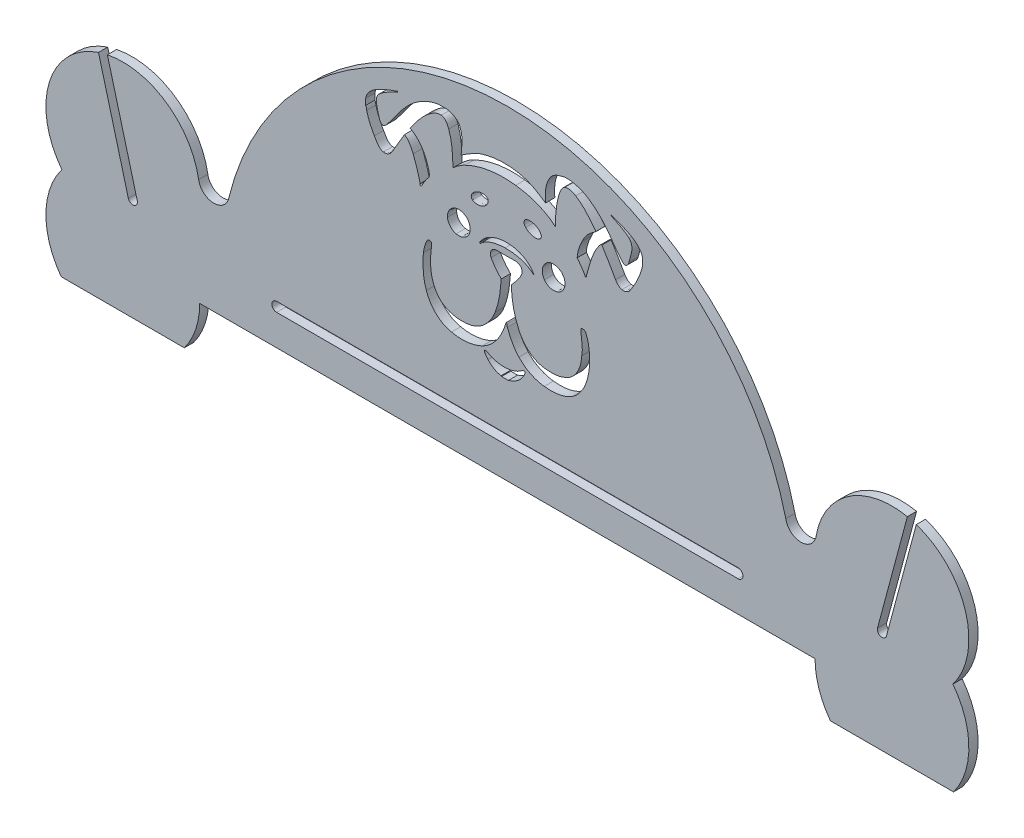
SolidWorks part; units mm, degrees
ref_plane "Plano frontal" through (0, 0, 0) normal (0, 0, 1) x (1, 0, 0)
ref_plane "Plano superior" through (0, 0, 0) normal (0, 1, 0) x (1, 0, 0)
ref_plane "Plano direito" through (0, 0, 0) normal (1, 0, 0) x (0, 0, -1)
sketch "Esboço1" plane through (0, 0, 0) normal (0, 0, 1) x (1, 0, 0)
  line L0 (-200, 0) -> (200, 0)
  line L1 (150, 26.2) -> (144.1525, 26.2)
  line L2 (0, 0) -> (0, 26.2) construction
  line L3 (150, 26.2) -> (-150, 26.2) construction
  line L4 (150, 20) -> (150, 26.2) construction
  line L5 (-144.1525, 26.2) -> (144.1525, 26.2)
  line L6 (150, 20) -> (-150, 20)
  line L13 (140, 61) -> (200, 61)
  line L14 (289.6201, 30.5) -> (200, 30.5) construction
  line L15 (200, 30.5) -> (200, 61) construction
  line L16 (250, 61) -> (262.9328, 109.2659) construction
  line L17 (210, -30) -> (290, -30)
  line L18 (260.0199, 109.9857) -> (240.6084, 37.5413)
  line L19 (246.404, 35.9884) -> (265.8154, 108.4328)
  line L20 (240.6084, 37.5413) -> (246.404, 35.9884) construction
  line L21 (243.5062, 36.7648) -> (250, 61) construction
  line L22 (-243.5062, 36.7648) -> (-250, 61) construction
  line L23 (-240.6084, 37.5413) -> (-246.404, 35.9884) construction
  line L24 (-250, 61) -> (-262.9328, 109.2659) construction
  line L25 (-200, 30.5) -> (-200, 61) construction
  line L26 (-289.6201, 30.5) -> (-200, 30.5) construction
  line L27 (-150, 20) -> (-150, 26.2) construction
  line L28 (-246.404, 35.9884) -> (-265.8154, 108.4328)
  line L29 (-260.0199, 109.9857) -> (-240.6084, 37.5413)
  line L30 (-210, -30) -> (-290, -30)
  line L31 (140, 61) -> (-200, 61)
  line L39 (-150, 26.2) -> (-144.1525, 26.2)
  arc A0 (150, 20) -> (150, 26.2) centre (150, 23.1) ccw
  arc A1 (200, 61) -> (260.0199, 109.9857) centre (250, 61) cw
  arc A2 (200, 0) -> (210, -30) centre (250, 0) ccw
  arc A3 (290, -30) -> (289.6201, 30.5) centre (250, 0) ccw
  arc A4 (240.6084, 37.5413) -> (246.404, 35.9884) centre (243.5062, 36.7648) ccw
  arc A5 (265.8154, 108.4328) -> (289.6201, 30.5) centre (250, 61) cw
  arc A6 (-265.8154, 108.4328) -> (-289.6201, 30.5) centre (-250, 61) ccw
  arc A7 (-240.6084, 37.5413) -> (-246.404, 35.9884) centre (-243.5062, 36.7648) cw
  arc A8 (-290, -30) -> (-289.6201, 30.5) centre (-250, 0) cw
  arc A9 (-200, 0) -> (-210, -30) centre (-250, 0) cw
  arc A10 (-200, 61) -> (-260.0199, 109.9857) centre (-250, 61) ccw
  arc A11 (-150, 20) -> (-150, 26.2) centre (-150, 23.1) cw
  point P45 (0, 20)
  point P54 (0, 20)
  dimension "D7" = 30
  dimension "D9" = 15
  dimension "D10" = 6
  dimension "D11" = 75
  dimension "D1" = 3.1
  dimension "D6" = 50
  dimension "D2" = 200
  dimension "D3" = 20
  dimension "D4" = 150
  dimension "D5" = 61
  dimension "D8" = 140
extrude "Ressalto-extrusão2" add sketch "Esboço1" along normal blind 6
sketch "Esboço7" plane through (0, 0, 6) normal (0, 0, 1) x (1, 0, 0)
  line L0 (0, 0) -> (0, 211) construction
  line L1 (200, 61) -> (-200, 61) construction
  line L2 (-200.6993, 69.3333) -> (-180.9791, 69.3333) construction
  line L3 (0, 211) -> (-172.3956, 211) construction
  line L4 (-200, 61) -> (-204.6025, 61)
  line L5 (-200, 61) -> (200, 61)
  line L6 (200, 61) -> (209.3232, 61)
  line L7 (209.3232, 61) -> (200.6993, 69.3333)
  line L8 (-204.6025, 61) -> (-204.6025, 69.3333)
  line L9 (-204.6025, 69.3333) -> (-200.6993, 69.3333)
  arc A0 (-200.6993, 69.3333) -> (-180.9791, 69.3333) centre (-190.8392, 71) ccw
  arc A1 (-200, 61) -> (-260.0199, 109.9857) centre (-250, 61) ccw construction
  arc A2 (-180.9791, 69.3333) -> (180.9791, 69.3333) centre (0, 24.5663) cw
  arc A3 (200.6993, 69.3333) -> (180.9791, 69.3333) centre (190.8392, 71) cw
  arc A4 (260.0199, 109.9857) -> (200, 61) centre (250, 61) ccw construction
  arc M8 (260.0199, 109.9857) -> (200, 61) centre (250, 61) ccw
  line M9 (200, 61) -> (-200, 61)
  arc M10 (-200, 61) -> (-260.0199, 109.9857) centre (-250, 61) ccw
  dimension "D2" = 10
  dimension "D1" = 211
extrude "Ressalto-extrusão4" add sketch "Esboço7" against normal up to vertex (6 mm away) contours L5 A3 A2 A0 | A3 M8 M9 | L6 L7 M8 | A0 L5 M10 | L9 L8 L4 M10
sketch "Esboço8" plane through (0, 0, 6) normal (0, 0, 1) x (1, 0, 0)
  line L0 (-44.7783, 189.7384) -> (-39.1773, 189.7384)
  line L1 (37.1274, 189.7384) -> (41.16, 189.7384)
  line L2 (87.8647, 169.7987) -> (87.8647, 165.1092)
  line L3 (-92.1581, 165.343) -> (-92.1581, 169.3644)
  line L4 (0.6392, 56.9718) -> (-3.8029, 56.9718)
  spline S0 degree 3 poles (-39.1773, 189.7384) (-36.0719, 189.0183) (-32.5885, 187.7289) (-31.1078, 184.635) knots 0.016129 0.016129 0.016129 0.016129 0.032258 0.032258 0.032258 0.032258
  spline S1 degree 3 poles (-31.1078, 184.635) (-28.6572, 179.6684) (-29.5867, 173.8604) (-30.0502, 168.5429) knots 0.032258 0.032258 0.032258 0.032258 0.048387 0.048387 0.048387 0.048387
  spline S2 degree 3 poles (-30.0502, 168.5429) (-25.9705, 171.0701) (-21.9875, 173.937) (-17.4035, 175.5257) knots 0.048387 0.048387 0.048387 0.048387 0.064516 0.064516 0.064516 0.064516
  spline S3 degree 3 poles (-17.4035, 175.5257) (-7.8804, 178.6176) (2.7207, 178.9302) (12.2934, 175.8452) knots 0.064516 0.064516 0.064516 0.064516 0.080645 0.080645 0.080645 0.080645
  spline S4 degree 3 poles (12.2934, 175.8452) (16.8276, 174.2565) (20.8602, 171.5855) (24.8432, 168.9706) knots 0.080645 0.080645 0.080645 0.080645 0.096774 0.096774 0.096774 0.096774
  spline S5 degree 3 poles (24.8432, 168.9706) (24.4225, 174.6706) (24.6092, 181.0503) (28.5111, 185.634) knots 0.096774 0.096774 0.096774 0.096774 0.112903 0.112903 0.112903 0.112903
  spline S6 degree 3 poles (28.5111, 185.634) (30.6353, 188.2645) (34.0312, 189.0002) (37.1274, 189.7384) knots 0.112903 0.112903 0.112903 0.112903 0.129032 0.129032 0.129032 0.129032
  spline S7 degree 3 poles (41.16, 189.7384) (43.8266, 189.0274) (46.7114, 188.6628) (49.2047, 187.3059) knots 0.145161 0.145161 0.145161 0.145161 0.16129 0.16129 0.16129 0.16129
  spline S8 degree 3 poles (49.2047, 187.3059) (55.9174, 184.0833) (61.3586, 178.7279) (65.742, 172.796) knots 0.16129 0.16129 0.16129 0.16129 0.177419 0.177419 0.177419 0.177419
  spline S9 degree 3 poles (65.742, 172.796) (68.8317, 168.6983) (71.4938, 164.2135) (75.1032, 160.5456) knots 0.177419 0.177419 0.177419 0.177419 0.193548 0.193548 0.193548 0.193548
  spline S10 degree 3 poles (75.1032, 160.5456) (76.8765, 158.5967) (78.7081, 161.0585) (79.039, 162.8047) knots 0.193548 0.193548 0.193548 0.193548 0.209677 0.209677 0.209677 0.209677
  spline S11 degree 3 poles (79.039, 162.8047) (80.0583, 167.0398) (82.6957, 172.562) (79.1313, 176.2749) knots 0.209677 0.209677 0.209677 0.209677 0.225806 0.225806 0.225806 0.225806
  spline S12 degree 3 poles (79.1313, 176.2749) (76.2463, 178.9372) (72.6324, 180.5842) (69.1196, 182.2427) knots 0.225806 0.225806 0.225806 0.225806 0.241935 0.241935 0.241935 0.241935
  spline S13 degree 3 poles (69.1196, 182.2427) (68.521, 182.5983) (67.567, 182.7177) (67.3555, 183.4578) knots 0.241935 0.241935 0.241935 0.241935 0.258065 0.258065 0.258065 0.258065
  spline S14 degree 3 poles (67.3555, 183.4578) (70.8704, 182.6117) (74.2684, 181.1738) (77.5561, 179.6528) knots 0.258065 0.258065 0.258065 0.258065 0.274194 0.274194 0.274194 0.274194
  spline S15 degree 3 poles (77.5561, 179.6528) (81.8832, 177.5598) (86.5324, 174.7224) (87.8647, 169.7987) knots 0.274194 0.274194 0.274194 0.274194 0.290323 0.290323 0.290323 0.290323
  spline S16 degree 3 poles (87.8647, 165.1092) (86.4175, 158.644) (83.4383, 152.5345) (79.6892, 147.0665) knots 0.306452 0.306452 0.306452 0.306452 0.322581 0.322581 0.322581 0.322581
  spline S17 degree 3 poles (79.6892, 147.0665) (78.4066, 145.597) (76.4669, 144.5415) (74.4596, 145.0478) knots 0.322581 0.322581 0.322581 0.322581 0.33871 0.33871 0.33871 0.33871
  spline S18 degree 3 poles (74.4596, 145.0478) (72.6009, 145.4574) (71.1877, 146.9178) (70.2989, 148.5424) knots 0.33871 0.33871 0.33871 0.33871 0.354839 0.354839 0.354839 0.354839
  spline S19 degree 3 poles (70.2989, 148.5424) (67.4612, 153.6169) (64.5921, 158.6823) (61.4305, 163.5654) knots 0.354839 0.354839 0.354839 0.354839 0.370968 0.370968 0.370968 0.370968
  spline S20 degree 3 poles (61.4305, 163.5654) (60.6811, 163.8736) (60.3009, 162.8071) (59.7967, 162.456) knots 0.370968 0.370968 0.370968 0.370968 0.387097 0.387097 0.387097 0.387097
  spline S21 degree 3 poles (59.7967, 162.456) (55.204, 156.5242) (53.5433, 149.0016) (51.5427, 141.9268) knots 0.387097 0.387097 0.387097 0.387097 0.403226 0.403226 0.403226 0.403226
  spline S22 degree 3 poles (51.5427, 141.9268) (51.3402, 141.7513) (51.4618, 139.6584) (50.6921, 140.4055) knots 0.403226 0.403226 0.403226 0.403226 0.419355 0.419355 0.419355 0.419355
  spline S23 degree 3 poles (50.6921, 140.4055) (49.2295, 143.2657) (47.2987, 145.8467) (45.4017, 148.4121) knots 0.419355 0.419355 0.419355 0.419355 0.435484 0.435484 0.435484 0.435484
  spline S24 degree 3 poles (45.4017, 148.4121) (45.4469, 152.2309) (46.9252, 155.8583) (48.5903, 159.2381) knots 0.435484 0.435484 0.435484 0.435484 0.451613 0.451613 0.451613 0.451613
  spline S25 degree 3 poles (48.5903, 159.2381) (50.2039, 162.8339) (52.7737, 166.0295) (56.1445, 168.1154) knots 0.451613 0.451613 0.451613 0.451613 0.467742 0.467742 0.467742 0.467742
  spline S26 degree 3 poles (56.1445, 168.1154) (56.6105, 168.453) (57.2135, 168.7208) (57.5127, 169.2519) knots 0.467742 0.467742 0.467742 0.467742 0.483871 0.483871 0.483871 0.483871
  spline S27 degree 3 poles (57.5127, 169.2519) (53.7818, 174.2722) (49.801, 179.4007) (44.4432, 182.7762) knots 0.483871 0.483871 0.483871 0.483871 0.5 0.5 0.5 0.5
  spline S28 degree 3 poles (44.4432, 182.7762) (41.9363, 184.2634) (38.1514, 185.5732) (35.9326, 182.9425) knots 0.5 0.5 0.5 0.5 0.516129 0.516129 0.516129 0.516129
  spline S29 degree 3 poles (35.9326, 182.9425) (33.626, 179.9476) (32.987, 176.1309) (32.2263, 172.5238) knots 0.516129 0.516129 0.516129 0.516129 0.532258 0.532258 0.532258 0.532258
  spline S30 degree 3 poles (32.2263, 172.5238) (31.6682, 167.9916) (31.0832, 163.4485) (31.1304, 158.8669) knots 0.532258 0.532258 0.532258 0.532258 0.548387 0.548387 0.548387 0.548387
  spline S31 degree 3 poles (31.1304, 158.8669) (23.9992, 165.0304) (14.7191, 168.0727) (5.4819, 169.2383) knots 0.548387 0.548387 0.548387 0.548387 0.564516 0.564516 0.564516 0.564516
  spline S32 degree 3 poles (5.4819, 169.2383) (-5.6999, 170.5659) (-17.4081, 169.1326) (-27.5524, 164.0537) knots 0.564516 0.564516 0.564516 0.564516 0.580645 0.580645 0.580645 0.580645
  spline S33 degree 3 poles (-27.5524, 164.0537) (-30.4733, 162.7014) (-33.0521, 160.7661) (-35.4149, 158.6079) knots 0.580645 0.580645 0.580645 0.580645 0.596774 0.596774 0.596774 0.596774
  spline S34 degree 3 poles (-35.4149, 158.6079) (-35.5071, 165.514) (-35.8267, 172.5847) (-38.1556, 179.1599) knots 0.596774 0.596774 0.596774 0.596774 0.612903 0.612903 0.612903 0.612903
  spline S35 degree 3 poles (-38.1556, 179.1599) (-39.0356, 181.3967) (-40.3071, 184.1081) (-42.96, 184.4773) knots 0.612903 0.612903 0.612903 0.612903 0.629032 0.629032 0.629032 0.629032
  spline S36 degree 3 poles (-42.96, 184.4773) (-45.8202, 184.7067) (-48.3405, 183.0304) (-50.5817, 181.4711) knots 0.629032 0.629032 0.629032 0.629032 0.645161 0.645161 0.645161 0.645161
  spline S37 degree 3 poles (-50.5817, 181.4711) (-55.6877, 177.5148) (-59.6886, 172.3349) (-63.3206, 167.0443) knots 0.645161 0.645161 0.645161 0.645161 0.66129 0.66129 0.66129 0.66129
  spline S38 degree 3 poles (-63.3206, 167.0443) (-56.2771, 163.6756) (-52.7083, 156.1148) (-50.8856, 148.9026) knots 0.66129 0.66129 0.66129 0.66129 0.677419 0.677419 0.677419 0.677419
  spline S39 degree 3 poles (-50.8856, 148.9026) (-50.8067, 147.6244) (-50.2847, 145.9211) (-51.4616, 144.9894) knots 0.677419 0.677419 0.677419 0.677419 0.693548 0.693548 0.693548 0.693548
  spline S40 degree 3 poles (-51.4616, 144.9894) (-53.1719, 142.946) (-54.5467, 140.644) (-55.7957, 138.2969) knots 0.693548 0.693548 0.693548 0.693548 0.709677 0.709677 0.709677 0.709677
  spline S41 degree 3 poles (-55.7957, 138.2969) (-56.0027, 137.6197) (-57.5712, 138.0111) (-56.6598, 139.0913) knots 0.709677 0.709677 0.709677 0.709677 0.725806 0.725806 0.725806 0.725806
  spline S42 degree 3 poles (-56.6598, 139.0913) (-57.938, 144.0038) (-59.2454, 148.9476) (-61.2414, 153.6258) knots 0.725806 0.725806 0.725806 0.725806 0.741935 0.741935 0.741935 0.741935
  spline S43 degree 3 poles (-61.2414, 153.6258) (-62.65, 156.5176) (-63.9754, 159.9875) (-66.8963, 161.5987) knots 0.741935 0.741935 0.741935 0.741935 0.758065 0.758065 0.758065 0.758065
  spline S44 degree 3 poles (-66.8963, 161.5987) (-69.349, 157.8835) (-71.4644, 153.9611) (-73.6674, 150.0952) knots 0.758065 0.758065 0.758065 0.758065 0.774194 0.774194 0.774194 0.774194
  spline S45 degree 3 poles (-73.6674, 150.0952) (-74.8961, 147.3948) (-77.2274, 144.2781) (-80.6455, 144.9917) knots 0.774194 0.774194 0.774194 0.774194 0.790323 0.790323 0.790323 0.790323
  spline S46 degree 3 poles (-80.6455, 144.9917) (-83.7171, 145.5722) (-84.9706, 148.7383) (-86.4671, 151.0853) knots 0.790323 0.790323 0.790323 0.790323 0.806452 0.806452 0.806452 0.806452
  spline S47 degree 3 poles (-86.4671, 151.0853) (-88.571, 154.8321) (-90.5198, 158.7475) (-91.4648, 162.9624) knots 0.806452 0.806452 0.806452 0.806452 0.822581 0.822581 0.822581 0.822581
  spline S48 degree 3 poles (-91.4648, 162.9624) (-91.6765, 163.7611) (-91.5278, 164.713) (-92.1581, 165.343) knots 0.822581 0.822581 0.822581 0.822581 0.83871 0.83871 0.83871 0.83871
  spline S49 degree 3 poles (-92.1581, 169.3644) (-91.1228, 174.8214) (-85.8324, 177.7714) (-81.1811, 179.9115) knots 0.854839 0.854839 0.854839 0.854839 0.870968 0.870968 0.870968 0.870968
  spline S50 degree 3 poles (-81.1811, 179.9115) (-78.3773, 181.2886) (-75.4203, 182.3103) (-72.4703, 183.3073) knots 0.870968 0.870968 0.870968 0.870968 0.887097 0.887097 0.887097 0.887097
  spline S51 degree 3 poles (-72.4703, 183.3073) (-71.0031, 184.4346) (-71.2753, 183.0145) (-71.8853, 182.9516) knots 0.887097 0.887097 0.887097 0.887097 0.903226 0.903226 0.903226 0.903226
  spline S52 degree 3 poles (-71.8853, 182.9516) (-75.8951, 181.0725) (-80.0694, 179.2342) (-83.3594, 176.2165) knots 0.903226 0.903226 0.903226 0.903226 0.919355 0.919355 0.919355 0.919355
  spline S53 degree 3 poles (-83.3594, 176.2165) (-86.3657, 173.4983) (-84.9346, 169.189) (-84.1807, 165.7977) knots 0.919355 0.919355 0.919355 0.919355 0.935484 0.935484 0.935484 0.935484
  spline S54 degree 3 poles (-84.1807, 165.7977) (-83.4809, 163.8828) (-83.3795, 161.5131) (-81.7302, 160.1089) knots 0.935484 0.935484 0.935484 0.935484 0.951613 0.951613 0.951613 0.951613
  spline S55 degree 3 poles (-81.7302, 160.1089) (-80.5893, 159.2583) (-79.2908, 160.4713) (-78.5842, 161.3129) knots 0.951613 0.951613 0.951613 0.951613 0.967742 0.967742 0.967742 0.967742
  spline S56 degree 3 poles (-78.5842, 161.3129) (-73.9014, 166.4593) (-70.724, 172.823) (-65.8049, 177.7826) knots 0.967742 0.967742 0.967742 0.967742 0.983871 0.983871 0.983871 0.983871
  spline S57 degree 3 poles (-65.8049, 177.7826) (-60.2962, 183.8585) (-52.9423, 188.5053) (-44.7783, 189.7384) knots 0.983871 0.983871 0.983871 0.983871 1 1 1 1
  spline S58 degree 3 poles (-18.2609, 153.6395) (-16.265, 153.8418) (-13.8459, 154.2491) (-12.534, 152.3185) knots 0 0 0 0 0.25 0.25 0.25 0.25
  spline S59 degree 3 poles (-12.534, 152.3185) (-11.7285, 147.3499) (-19.0688, 144.4649) (-22.6873, 146.9134) knots 0.25 0.25 0.25 0.25 0.5 0.5 0.5 0.5
  spline S60 degree 3 poles (-22.6873, 146.9134) (-23.7629, 147.746) (-23.6819, 149.4268) (-22.9416, 150.4485) knots 0.5 0.5 0.5 0.5 0.75 0.75 0.75 0.75
  spline S61 degree 3 poles (-22.9416, 150.4485) (-21.893, 152.1116) (-20.0027, 152.9014) (-18.2609, 153.6395) knots 0.75 0.75 0.75 0.75 1 1 1 1
  spline S62 degree 3 poles (12.7861, 153.6574) (16.0017, 154.2942) (20.0275, 153.1151) (21.6524, 150.1042) knots 0 0 0 0 0.25 0.25 0.25 0.25
  spline S63 degree 3 poles (21.6524, 150.1042) (22.4804, 148.8013) (21.9921, 146.9089) (20.4619, 146.398) knots 0.25 0.25 0.25 0.25 0.5 0.5 0.5 0.5
  spline S64 degree 3 poles (20.4619, 146.398) (17.4735, 145.3427) (13.9159, 146.4789) (11.8522, 148.8306) knots 0.5 0.5 0.5 0.5 0.75 0.75 0.75 0.75
  spline S65 degree 3 poles (11.8522, 148.8306) (10.2006, 150.219) (10.617, 153.1488) (12.7861, 153.6574) knots 0.75 0.75 0.75 0.75 1 1 1 1
  spline S66 degree 3 poles (-33.1129, 136.9828) (-30.4395, 137.5972) (-27.6942, 136.4473) (-25.8309, 134.5592) knots 0 0 0 0 0.2 0.2 0.2 0.2
  spline S67 degree 3 poles (-25.8309, 134.5592) (-24.3953, 132.4483) (-23.5785, 129.6267) (-24.6316, 127.1716) knots 0.2 0.2 0.2 0.2 0.4 0.4 0.4 0.4
  spline S68 degree 3 poles (-24.6316, 127.1716) (-25.7477, 123.7512) (-29.8454, 121.6518) (-33.2883, 122.5722) knots 0.4 0.4 0.4 0.4 0.6 0.6 0.6 0.6
  spline S69 degree 3 poles (-33.2883, 122.5722) (-36.3037, 123.1977) (-38.698, 126.0015) (-38.9569, 129.0663) knots 0.6 0.6 0.6 0.6 0.8 0.8 0.8 0.8
  spline S70 degree 3 poles (-38.9569, 129.0663) (-39.2471, 132.6397) (-36.675, 136.2764) (-33.1129, 136.9828) knots 0.8 0.8 0.8 0.8 1 1 1 1
  spline S71 degree 3 poles (28.3221, 136.9805) (31.279, 137.4982) (34.8096, 136.4542) (36.2836, 133.657) knots 0 0 0 0 0.25 0.25 0.25 0.25
  spline S72 degree 3 poles (36.2836, 133.657) (38.1108, 131.0983) (37.8025, 127.4078) (35.7682, 125.0565) knots 0.25 0.25 0.25 0.25 0.5 0.5 0.5 0.5
  spline S73 degree 3 poles (35.7682, 125.0565) (32.906, 121.3614) (26.6592, 121.4741) (24.0421, 125.4613) knots 0.5 0.5 0.5 0.5 0.75 0.75 0.75 0.75
  spline S74 degree 3 poles (24.0421, 125.4613) (20.9682, 129.5164) (23.4098, 135.8238) (28.3221, 136.9805) knots 0.75 0.75 0.75 0.75 1 1 1 1
  spline S75 degree 3 poles (-4.3025, 133.8212) (3.6545, 134.9509) (12.9077, 132.4777) (17.1742, 125.1283) knots 0 0 0 0 0.166667 0.166667 0.166667 0.166667
  spline S76 degree 3 poles (17.1742, 125.1283) (17.4038, 124.7279) (16.6049, 124.9528) (16.4744, 125.1059) knots 0.166667 0.166667 0.166667 0.166667 0.333333 0.333333 0.333333 0.333333
  spline S77 degree 3 poles (16.4744, 125.1059) (11.6453, 129.4759) (4.7999, 130.5696) (-1.4693, 130.5337) knots 0.333333 0.333333 0.333333 0.333333 0.5 0.5 0.5 0.5
  spline S78 degree 3 poles (-1.4693, 130.5337) (-6.9082, 130.3693) (-12.705, 129.1878) (-16.94, 125.5516) knots 0.5 0.5 0.5 0.5 0.666667 0.666667 0.666667 0.666667
  spline S79 degree 3 poles (-16.94, 125.5516) (-17.1605, 125.2049) (-18.0428, 124.541) (-18.1237, 125.1531) knots 0.666667 0.666667 0.666667 0.666667 0.833333 0.833333 0.833333 0.833333
  spline S80 degree 3 poles (-18.1237, 125.1531) (-15.3919, 130.1196) (-9.8021, 132.9773) (-4.3025, 133.8212) knots 0.833333 0.833333 0.833333 0.833333 1 1 1 1
  spline S81 degree 3 poles (-7.4596, 126.4065) (-3.3709, 126.6361) (0.736, 126.4447) (4.8314, 126.51) knots 0 0 0 0 0.035714 0.035714 0.035714 0.035714
  spline S82 degree 3 poles (4.8314, 126.51) (6.2379, 126.4786) (7.7972, 126.1118) (8.7515, 125.0181) knots 0.035714 0.035714 0.035714 0.035714 0.071429 0.071429 0.071429 0.071429
  spline S83 degree 3 poles (8.7515, 125.0181) (9.9283, 123.4451) (9.593, 121.3478) (8.6861, 119.7277) knots 0.071429 0.071429 0.071429 0.071429 0.107143 0.107143 0.107143 0.107143
  spline S84 degree 3 poles (8.6861, 119.7277) (7.0592, 116.8091) (4.8156, 114.3066) (2.6396, 111.7932) knots 0.107143 0.107143 0.107143 0.107143 0.142857 0.142857 0.142857 0.142857
  spline S85 degree 3 poles (2.6396, 111.7932) (2.7364, 104.0656) (4.0664, 96.2348) (7.3451, 89.1845) knots 0.142857 0.142857 0.142857 0.142857 0.178571 0.178571 0.178571 0.178571
  spline S86 degree 3 poles (7.3451, 89.1845) (10.187, 82.4561) (16.1752, 76.7517) (23.5719, 75.7122) knots 0.178571 0.178571 0.178571 0.178571 0.214286 0.214286 0.214286 0.214286
  spline S87 degree 3 poles (23.5719, 75.7122) (28.0768, 75.1474) (32.9938, 75.0417) (37.2332, 76.9994) knots 0.214286 0.214286 0.214286 0.214286 0.25 0.25 0.25 0.25
  spline S88 degree 3 poles (37.2332, 76.9994) (44.4071, 79.4836) (48.0706, 87.3933) (48.2844, 94.5492) knots 0.25 0.25 0.25 0.25 0.285714 0.285714 0.285714 0.285714
  spline S89 degree 3 poles (48.2844, 94.5492) (49.4951, 99.6056) (47.67, 104.7272) (47.841, 109.8106) knots 0.285714 0.285714 0.285714 0.285714 0.321429 0.321429 0.321429 0.321429
  spline S90 degree 3 poles (47.841, 109.8106) (49.0113, 110.4698) (50.5527, 110.1123) (51.0431, 108.807) knots 0.321429 0.321429 0.321429 0.321429 0.357143 0.357143 0.357143 0.357143
  spline S91 degree 3 poles (51.0431, 108.807) (53.3542, 103.5774) (53.5005, 97.7245) (53.3879, 92.1008) knots 0.357143 0.357143 0.357143 0.357143 0.392857 0.392857 0.392857 0.392857
  spline S92 degree 3 poles (53.3879, 92.1008) (52.9357, 83.4891) (49.8821, 74.1775) (42.5642, 68.9794) knots 0.392857 0.392857 0.392857 0.392857 0.428571 0.428571 0.428571 0.428571
  spline S93 degree 3 poles (42.5642, 68.9794) (37.1455, 65.3205) (30.2754, 64.49) (23.9543, 65.2866) knots 0.428571 0.428571 0.428571 0.428571 0.464286 0.464286 0.464286 0.464286
  spline S94 degree 3 poles (23.9543, 65.2866) (17.7548, 65.9775) (11.7218, 68.9163) (7.4755, 73.5655) knots 0.464286 0.464286 0.464286 0.464286 0.5 0.5 0.5 0.5
  spline S95 degree 3 poles (7.4755, 73.5655) (3.9943, 77.2514) (1.6473, 81.8374) (0, 86.5923) knots 0.5 0.5 0.5 0.5 0.535714 0.535714 0.535714 0.535714
  spline S96 degree 3 poles (0, 86.5923) (-0.477, 87.2269) (0.0181, 89.0247) (-0.8663, 88.775) knots 0.535714 0.535714 0.535714 0.535714 0.571429 0.571429 0.571429 0.571429
  spline S97 degree 3 poles (-0.8663, 88.775) (-3.2336, 80.3252) (-8.1414, 71.9903) (-16.274, 67.9598) knots 0.571429 0.571429 0.571429 0.571429 0.607143 0.607143 0.607143 0.607143
  spline S98 degree 3 poles (-16.274, 67.9598) (-22.442, 64.9851) (-29.7081, 64.193) (-36.3533, 65.7345) knots 0.607143 0.607143 0.607143 0.607143 0.642857 0.642857 0.642857 0.642857
  spline S99 degree 3 poles (-36.3533, 65.7345) (-44.092, 67.2331) (-50.2262, 73.5856) (-52.6678, 80.9666) knots 0.642857 0.642857 0.642857 0.642857 0.678571 0.678571 0.678571 0.678571
  spline S100 degree 3 poles (-52.6678, 80.9666) (-55.0261, 87.416) (-55.1251, 94.3942) (-54.6503, 101.1472) knots 0.678571 0.678571 0.678571 0.678571 0.714286 0.714286 0.714286 0.714286
  spline S101 degree 3 poles (-54.6503, 101.1472) (-54.126, 104.0117) (-53.6082, 107.045) (-52.0535, 109.5766) knots 0.714286 0.714286 0.714286 0.714286 0.75 0.75 0.75 0.75
  spline S102 degree 3 poles (-52.0535, 109.5766) (-51.3131, 110.6051) (-48.8805, 110.3463) (-49.218, 108.7575) knots 0.75 0.75 0.75 0.75 0.785714 0.785714 0.785714 0.785714
  spline S103 degree 3 poles (-49.218, 108.7575) (-50.3545, 99.6573) (-50.9666, 89.1689) (-44.8414, 81.5606) knots 0.785714 0.785714 0.785714 0.785714 0.821429 0.821429 0.821429 0.821429
  spline S104 degree 3 poles (-44.8414, 81.5606) (-39.8209, 75.4736) (-31.0223, 74.4678) (-23.7471, 75.8944) knots 0.821429 0.821429 0.821429 0.821429 0.857143 0.857143 0.857143 0.857143
  spline S105 degree 3 poles (-23.7471, 75.8944) (-16.148, 77.6451) (-10.6168, 84.072) (-7.9232, 91.1356) knots 0.857143 0.857143 0.857143 0.857143 0.892857 0.892857 0.892857 0.892857
  spline S106 degree 3 poles (-7.9232, 91.1356) (-5.3645, 97.7423) (-4.4218, 104.7904) (-3.9784, 111.8134) knots 0.892857 0.892857 0.892857 0.892857 0.928571 0.928571 0.928571 0.928571
  spline S107 degree 3 poles (-3.9784, 111.8134) (-6.6316, 114.3088) (-8.8323, 117.3313) (-10.6168, 120.5017) knots 0.928571 0.928571 0.928571 0.928571 0.964286 0.964286 0.964286 0.964286
  spline S108 degree 3 poles (-10.6168, 120.5017) (-11.9444, 122.9208) (-10.2702, 126.2557) (-7.4596, 126.4065) knots 0.964286 0.964286 0.964286 0.964286 1 1 1 1
  spline S109 degree 3 poles (10.0184, 67.287) (10.3535, 67.2982) (11.022, 67.3186) (11.355, 67.3298) knots 0 0 0 0 0.111111 0.111111 0.111111 0.111111
  spline S110 degree 3 poles (11.355, 67.3298) (11.6588, 65.516) (10.3267, 64.1504) (9.4153, 62.7462) knots 0.111111 0.111111 0.111111 0.111111 0.222222 0.222222 0.222222 0.222222
  spline S111 degree 3 poles (9.4153, 62.7462) (7.3045, 59.8116) (4.0349, 57.9664) (0.6392, 56.9718) knots 0.222222 0.222222 0.222222 0.222222 0.333333 0.333333 0.333333 0.333333
  spline S112 degree 3 poles (-3.8029, 56.9718) (-3.866, 57.0573) (-3.9942, 57.2306) (-4.0572, 57.3161) knots 0.444444 0.444444 0.444444 0.444444 0.555556 0.555556 0.555556 0.555556
  spline S113 degree 3 poles (-4.0572, 57.3161) (-7.3921, 57.676) (-10.3468, 59.6519) (-12.5632, 62.0846) knots 0.555556 0.555556 0.555556 0.555556 0.666667 0.666667 0.666667 0.666667
  spline S114 degree 3 poles (-12.5632, 62.0846) (-13.4003, 63.3378) (-15.3243, 64.7105) (-14.7101, 66.4118) knots 0.666667 0.666667 0.666667 0.666667 0.777778 0.777778 0.777778 0.777778
  spline S115 degree 3 poles (-14.7101, 66.4118) (-12.9637, 66.6952) (-11.7577, 65.1382) (-10.1599, 64.7354) knots 0.777778 0.777778 0.777778 0.777778 0.888889 0.888889 0.888889 0.888889
  spline S116 degree 3 poles (-10.1599, 64.7354) (-3.5959, 62.1069) (4.4444, 62.719) (10.0184, 67.287) knots 0.888889 0.888889 0.888889 0.888889 1 1 1 1
extrude "Corte-extrusão1" cut sketch "Esboço8" against normal through all
